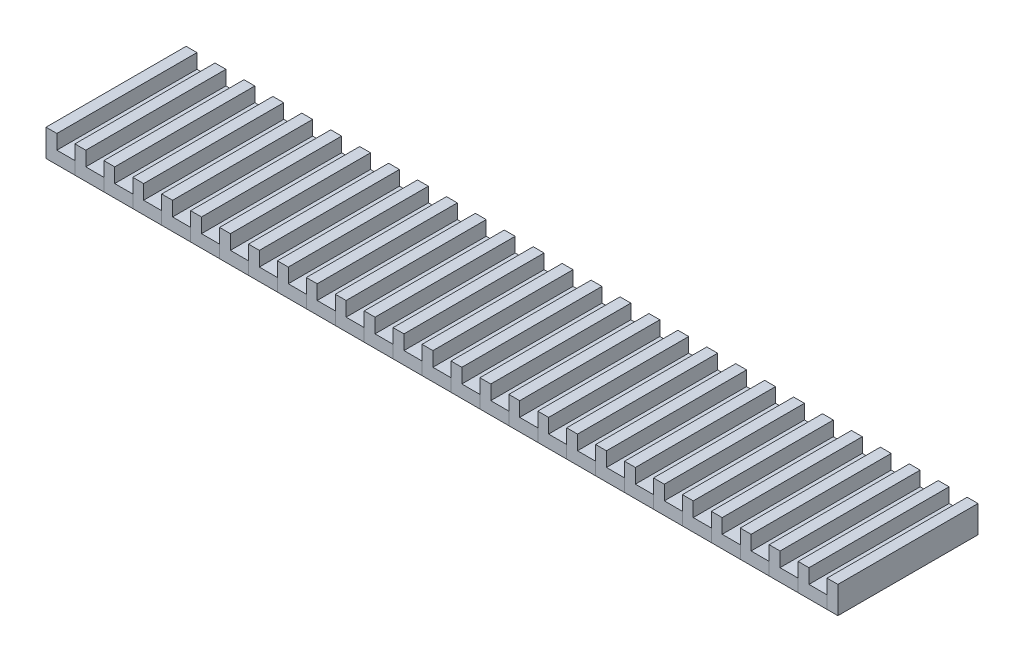
SolidWorks part; units mm, degrees
ref_plane "Front Plane" through (0, 0, 0) normal (0, 0, 1) x (1, 0, 0)
ref_plane "Top Plane" through (0, 0, 0) normal (0, 1, 0) x (1, 0, 0)
ref_plane "Right Plane" through (0, 0, 0) normal (1, 0, 0) x (0, 0, -1)
sketch "Sketch1" plane through (0, 0, 0) normal (0, 1, 0) x (1, 0, 0)
  line L1 (0, 0) -> (6.4, 0)
  line L2 (0, 0) -> (0, 31)
  line L3 (0, 31) -> (6.4, 31)
  line L4 (6.4, 0) -> (6.4, 31)
  dimension "D1" = 31
  dimension "D2" = 6.4
extrude "Boss-Extrude1" add sketch "Sketch1" along normal blind 6
sketch "Sketch2" plane through (0, 0, 0) normal (0, 1, 0) x (1, 0, 0)
  line L0 (0, 0) -> (6.4, 0) construction
  line L1 (6.4, 31) -> (2.4, 31)
  line L2 (6.4, 31) -> (6.4, 0)
  line L3 (6.4, 0) -> (2.4, 0)
  line L4 (2.4, 31) -> (2.4, 0)
  dimension "D1" = 4
extrude "Cut-Extrude1" cut sketch "Sketch2" along normal blind 10 from offset 2.8
pattern_linear "LPattern1" count 28 spacing 6.4 along (1, 0, 0) of "Boss-Extrude1"
sketch "Sketch3" plane through (0, 2.8, 0) normal (0, 1, 0) x (1, 0, 0)
  line L1 (179.2, 31) -> (175.2, 31)
  line L2 (179.2, 31) -> (179.2, 0)
  line L3 (179.2, 0) -> (175.2, 0)
  line L4 (175.2, 31) -> (175.2, 0)
  point P4 (200.8, 26.5193)
  point P5 (0, 0)
  point P8 (175.2, 0)
  point P10 (179.2, 31)
extrude "Cut-Extrude2" cut sketch "Sketch3" against normal blind 10
